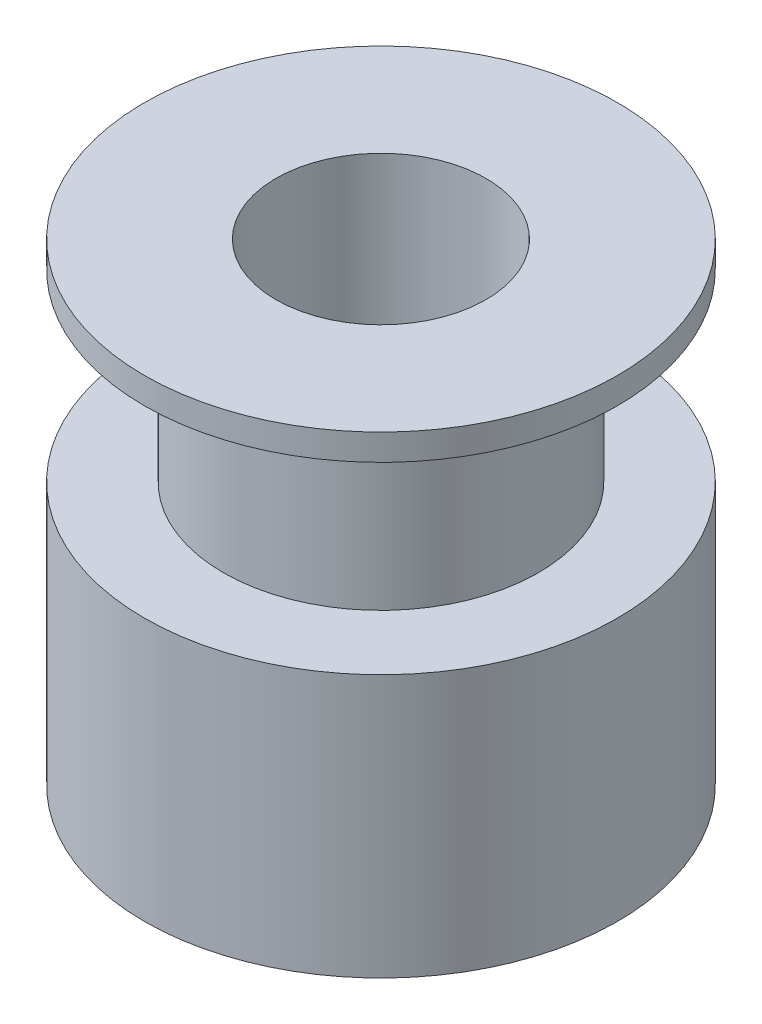
SolidWorks part; units mm, degrees
ref_plane "Front Plane" through (0, 0, 0) normal (0, 0, 1) x (1, 0, 0)
ref_plane "Top Plane" through (0, 0, 0) normal (0, 1, 0) x (1, 0, 0)
ref_plane "Right Plane" through (0, 0, 0) normal (1, 0, 0) x (0, 0, -1)
sketch "Sketch1" plane through (0, 0, 0) normal (0, 1, 0) x (1, 0, 0)
  circle A0 centre (0, 0) radius 9
  dimension "D1" = 18
extrude "Boss-Extrude1" add sketch "Sketch1" along normal blind 18
sketch "Sketch2" plane through (0, 18, 0) normal (0, 1, 0) x (1, 0, 0)
  circle A1 centre (0, 0) radius 4
  dimension "D1" = 8
extrude "Cut-Extrude1" cut sketch "Sketch2" against normal through all
sketch "Sketch3" plane through (0, 18, 0) normal (0, 1, 0) x (1, 0, 0)
  circle A0 centre (0, 0) radius 10
  circle A1 centre (0, 0) radius 6
  dimension "D1" = 12
  dimension "D2" = 20
extrude "Cut-Extrude2" cut sketch "Sketch3" against normal blind 7 from offset 1
